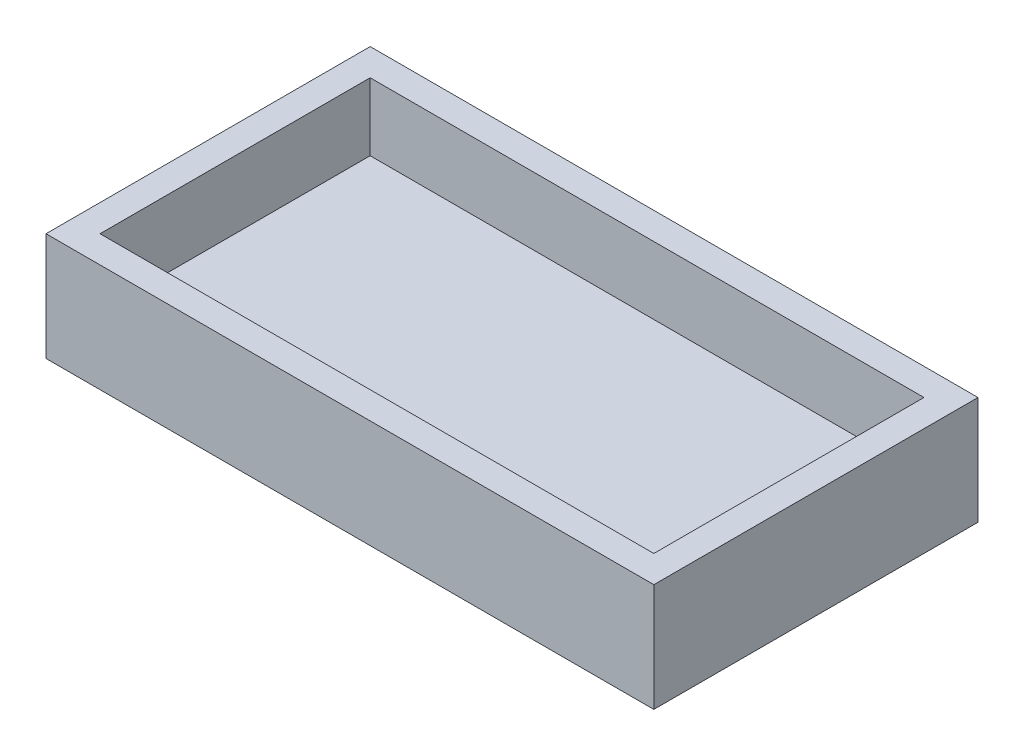
SolidWorks part; units mm, degrees
ref_plane "Front Plane" through (0, 0, 0) normal (0, 0, 1) x (1, 0, 0)
ref_plane "Top Plane" through (0, 0, 0) normal (0, 1, 0) x (1, 0, 0)
ref_plane "Right Plane" through (0, 0, 0) normal (1, 0, 0) x (0, 0, -1)
sketch "Sketch1" plane through (0, 0, 0) normal (0, 1, 0) x (1, 0, 0)
  line L1 (-20.5, 10) -> (20.5, 10)
  line L2 (-20.5, 10) -> (-20.5, -10)
  line L3 (-20.5, -10) -> (20.5, -10)
  line L4 (20.5, 10) -> (20.5, -10)
  line L5 (-20.5, 10) -> (20.5, -10) construction
  line L6 (-20.5, -10) -> (20.5, 10) construction
  point P0 (0, 0)
extrude "Boss-Extrude1" add sketch "Sketch1" along normal blind 3
sketch "Sketch2" plane through (0, 0, 0) normal (0, -1, 0) x (1, 0, 0)
  line L0 (-20.5, -10) -> (-20.5, 10) construction
  line L1 (20.5, -10) -> (-20.5, -10)
  line L2 (20.5, -10) -> (20.5, 10)
  line L3 (20.5, 10) -> (-20.5, 10)
  line L4 (-20.5, -10) -> (-20.5, 10)
  line L9 (22.5, -12) -> (22.5, 12)
  line L14 (22.5, 12) -> (-22.5, 12)
  line L15 (-22.5, -12) -> (-22.5, 12)
  line L16 (22.5, -12) -> (-22.5, -12)
  dimension "D2" = 2
extrude "Boss-Extrude2" add sketch "Sketch2" against normal offset from surface (8 mm away) 5 up to face at (0, 3, 0) offset beyond the face yes
